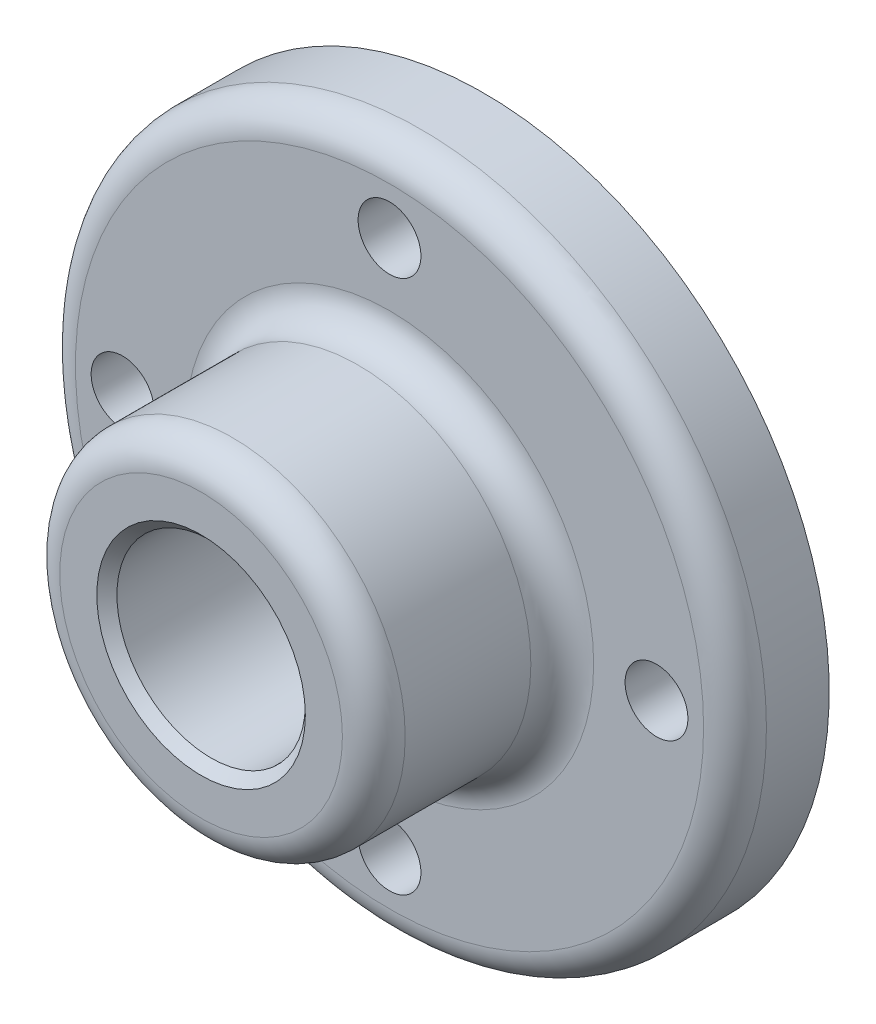
SolidWorks part; units mm, degrees
ref_plane "Front Plane" through (0, 0, 0) normal (0, 0, 1) x (1, 0, 0)
ref_plane "Top Plane" through (0, 0, 0) normal (0, 1, 0) x (1, 0, 0)
ref_plane "Right Plane" through (0, 0, 0) normal (1, 0, 0) x (0, 0, -1)
sketch "Sketch1" plane through (0, 0, 0) normal (0, 0, 1) x (1, 0, 0)
  circle A0 centre (0, 0) radius 69.85
  dimension "D1" = 139.7
extrude "Boss-Extrude1" add sketch "Sketch1" along normal blind 19.05
ref_plane "Plane1" through (0, 0, 57.15) normal (0, 0, 1) x (1, 0, 0)
sketch "Sketch2" plane through (0, 0, 57.15) normal (0, 0, 1) x (1, 0, 0)
  circle A0 centre (0, 0) radius 34.925
  dimension "D1" = 69.85
extrude "Boss-Extrude2" add sketch "Sketch2" against normal up to next
sketch "Sketch5" plane through (0, 0, 57.15) normal (0, 0, 1) x (1, 0, 0)
  circle A0 centre (0, 0) radius 19.05
  dimension "D1" = 38.1
extrude "Cut-Extrude1" cut sketch "Sketch5" against normal through all
sketch "Sketch6" plane through (0, 0, 19.05) normal (0, 0, 1) x (1, 0, 0)
  circle A0 centre (0, 0) radius 53.975 construction
  circle A1 centre (0, 53.975) radius 6.35
  dimension "D1" = 107.95
  dimension "D2" = 12.7
extrude "Bolt hole" cut sketch "Sketch6" against normal through all and the other way through all
pattern_circular "CirPattern1" count 4 over 360 about axis through (0, 0, 0) along (0, 0, 1) of "Bolt hole"
fillet "Fillet1" radius 6.35 3 edges at (69.85, 0, 19.05) (34.925, 0, 19.05) (34.925, 0, 57.15)
chamfer "Chamfer1" distance 2.032 angle 45 1 edges at (19.05, 0, 57.15)
